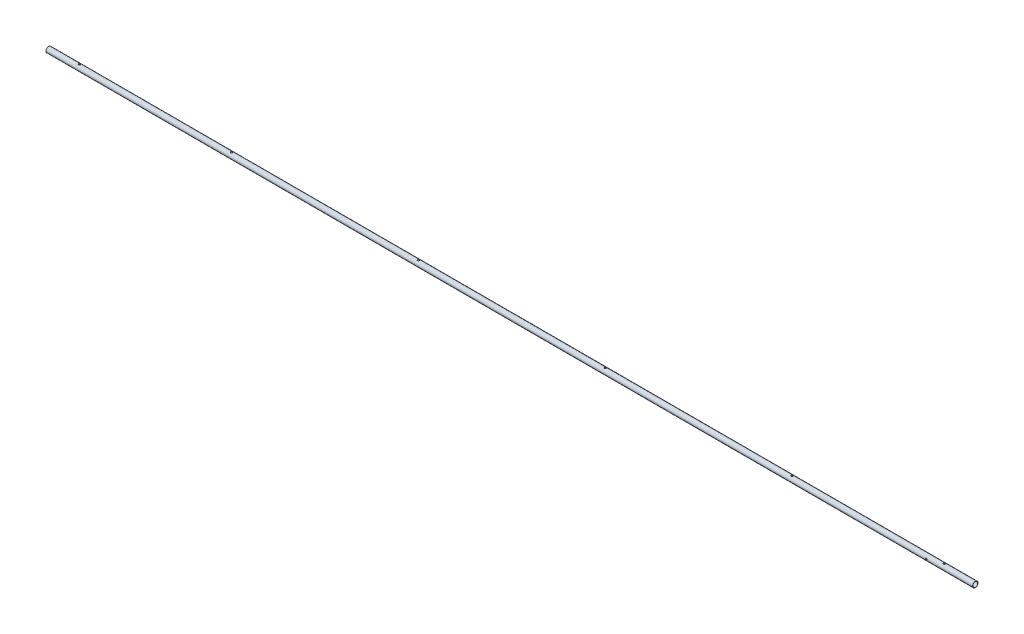
SolidWorks part; units mm, degrees
material "Galvanized Steel"
ref_plane "Front Plane" through (0, 0, 0) normal (0, 0, 1) x (1, 0, 0)
ref_plane "Top Plane" through (0, 0, 0) normal (0, 1, 0) x (1, 0, 0)
ref_plane "Right Plane" through (0, 0, 0) normal (1, 0, 0) x (0, 0, -1)
sketch "Sketch1" plane through (0, 0, 0) normal (1, 0, 0) x (0, 0, -1)
  circle A0 centre (0, 0) radius 7.8994
  circle A1 centre (0, 0) radius 8.9662
  dimension "D1" = 15.7988
  dimension "D2" = 17.9324
extrude "Boss-Extrude1" add sketch "Sketch1" along normal blind 3048
sketch "Sketch2" plane through (0, 0, 0) normal (0, 1, 0) x (1, 0, 0)
  line L0 (0, 8.9662) -> (0, -8.9662) construction
  line L1 (3048, -8.9662) -> (3048, 8.9662) construction
  circle A0 centre (601.98, 0) radius 3.175
  circle A1 centre (1216.66, 0) radius 3.175
  circle A2 centre (101.6, 0) radius 3.175
  circle A3 centre (2946.4, 0) radius 3.175
  circle A5 centre (2446.02, 0) radius 3.175
  circle A6 centre (1831.34, 0) radius 3.175
  dimension "D1" = 500.38
  dimension "D3" = 614.68
  dimension "D5" = 6.35
  dimension "D7" = 6.35
  dimension "D9" = 614.68
  dimension "D2" = 614.68
  dimension "D6" = 101.6
  dimension "D8" = 101.6
extrude "Cut-Extrude5" cut sketch "Sketch2" against normal through all and the other way through all
sketch "Sketch3" plane through (0, 0, 0) normal (0, 0, 1) x (1, 0, 0)
  line L0 (3048, -8.9662) -> (3048, 8.9662) construction
  circle A0 centre (2895.6, 0) radius 3.175
  dimension "D1" = 152.4
extrude "Cut-Extrude6" cut sketch "Sketch3" against normal through all and the other way through all
